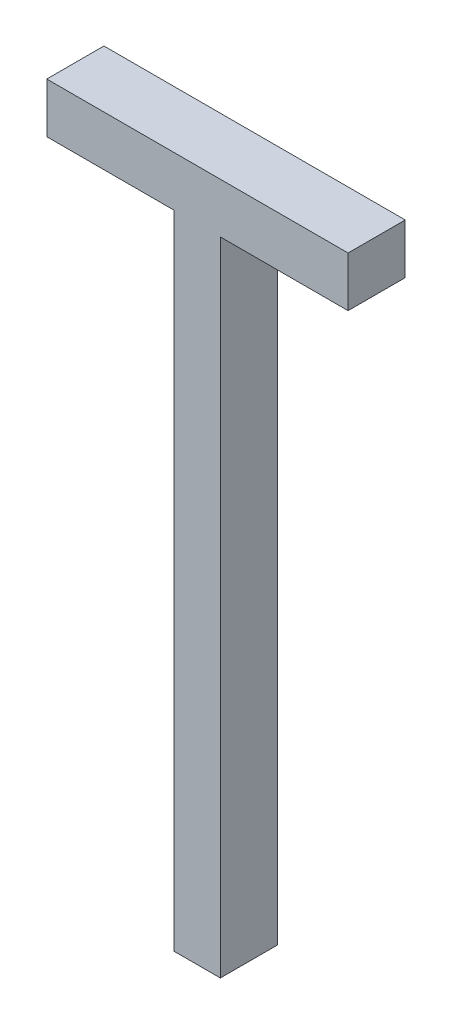
SolidWorks part; units mm, degrees
ref_plane "Спереди" through (0, 0, 0) normal (0, 0, 1) x (1, 0, 0)
ref_plane "Сверху" through (0, 0, 0) normal (0, 1, 0) x (1, 0, 0)
ref_plane "Справа" through (0, 0, 0) normal (1, 0, 0) x (0, 0, -1)
sketch "Эскиз1" plane through (0, 0, 0) normal (0, 0, 1) x (1, 0, 0)
  line L1 (-88.937, 112.165) -> (121.8476, 112.165)
  line L2 (-88.937, 112.165) -> (-88.937, 77.2104)
  line L3 (-88.937, 77.2104) -> (121.8476, 77.2104)
  line L4 (121.8476, 112.165) -> (121.8476, 77.2104)
  line L5 (0, 77.2104) -> (32.4988, 77.2104)
  line L6 (0, 77.2104) -> (0, -371.7496)
  line L7 (0, -371.7496) -> (32.4988, -371.7496)
  line L8 (32.4988, 77.2104) -> (32.4988, -371.7496)
extrude "Бобышка-Вытянуть1" add sketch "Эскиз1" along normal blind 40 contours L8 L3 L6 L7
